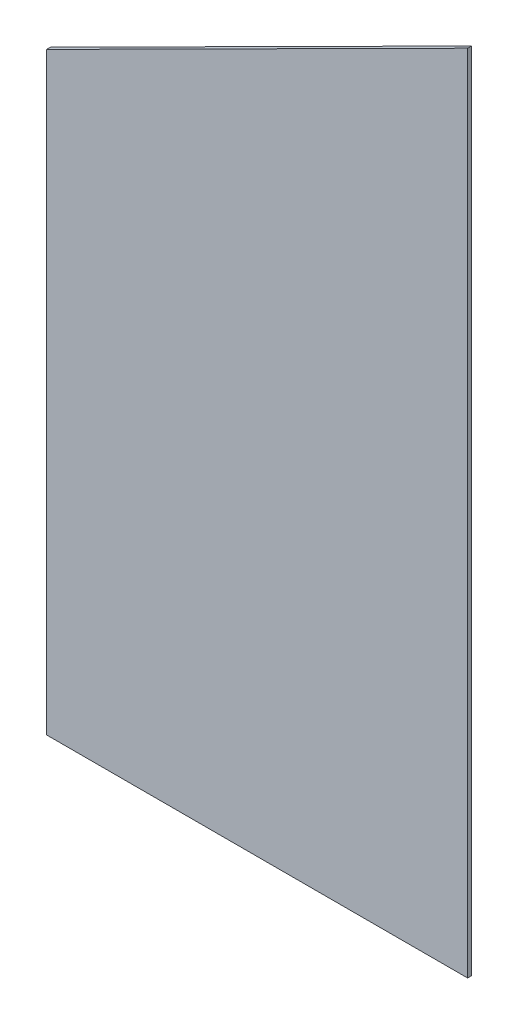
SolidWorks part; units mm, degrees
ref_plane "Plan de face" through (0, 0, 0) normal (0, 0, 1) x (1, 0, 0)
ref_plane "Plan de dessus" through (0, 0, 0) normal (0, 1, 0) x (1, 0, 0)
ref_plane "Plan de droite" through (0, 0, 0) normal (1, 0, 0) x (0, 0, -1)
sketch "Esquisse1" plane through (0, 0, 0) normal (0, 0, 1) x (1, 0, 0)
  line L0 (-177.6232, 0) -> (193.2536, 0) construction
  line L1 (0, 106.6229) -> (0, -104.4702) construction
  line L3 (-110, -210) -> (110, -210)
  line L4 (110, -210) -> (110, 210)
  line L8 (-109.6064, -210.3388) -> (-109.6064, 99.6612)
  line L10 (-109.6064, 99.6612) -> (110, 210)
  line L11 (-109.6064, 99.6612) -> (110, 210)
  line L12 (110, -210) -> (-110, -210)
extrude "Boss.-Extru.1" add sketch "Esquisse1" along normal blind 2 contours L10 L8 L3 L4
